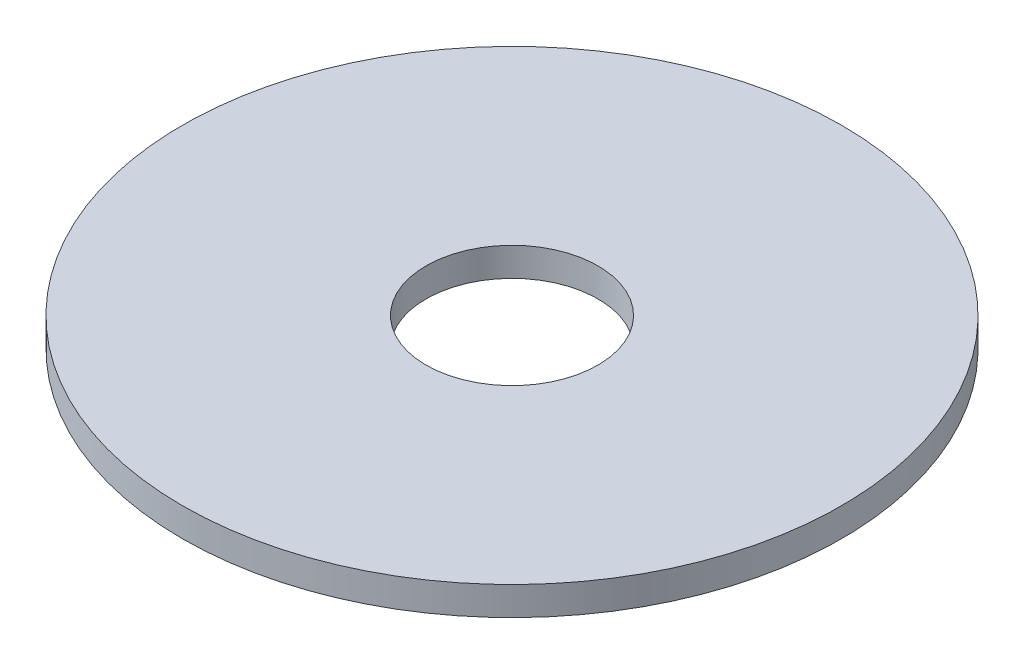
SolidWorks part; units mm, degrees
ref_plane "Front Plane" through (0, 0, 0) normal (0, 0, 1) x (1, 0, 0)
ref_plane "Top Plane" through (0, 0, 0) normal (0, 1, 0) x (1, 0, 0)
ref_plane "Right Plane" through (0, 0, 0) normal (1, 0, 0) x (0, 0, -1)
sketch "Sketch1" plane through (0, 0, 0) normal (0, 1, 0) x (1, 0, 0)
  circle A0 centre (0, 0) radius 14.605
  circle A1 centre (0, 0) radius 3.81
extrude "Boss-Extrude1" add sketch "Sketch1" along normal blind 1.27
